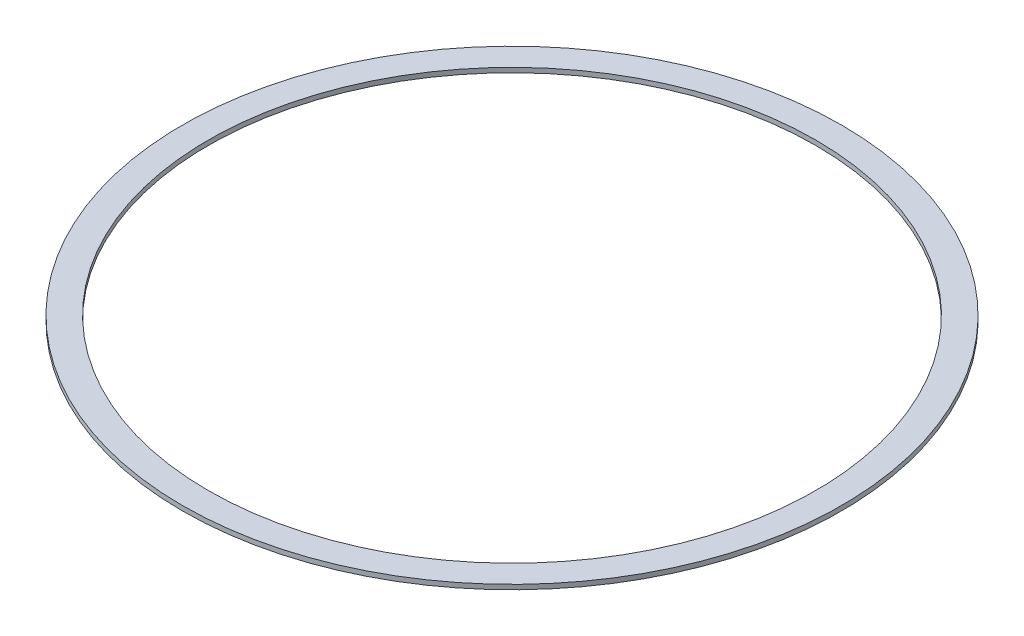
SolidWorks part; units mm, degrees
ref_plane "前视基准面" through (0, 0, 0) normal (0, 0, 1) x (1, 0, 0)
ref_plane "上视基准面" through (0, 0, 0) normal (0, 1, 0) x (1, 0, 0)
ref_plane "右视基准面" through (0, 0, 0) normal (1, 0, 0) x (0, 0, -1)
other "Configuration Table"
sketch "草图1" plane through (0, 0, 0) normal (0, 1, 0) x (1, 0, 0)
  circle A0 centre (0, 0) radius 32.25
  circle A1 centre (0, 0) radius 35
  dimension "D1" = 64.5
  dimension "D2" = 70
extrude "凸台-拉伸1" add sketch "草图1" along normal blind 0.5
